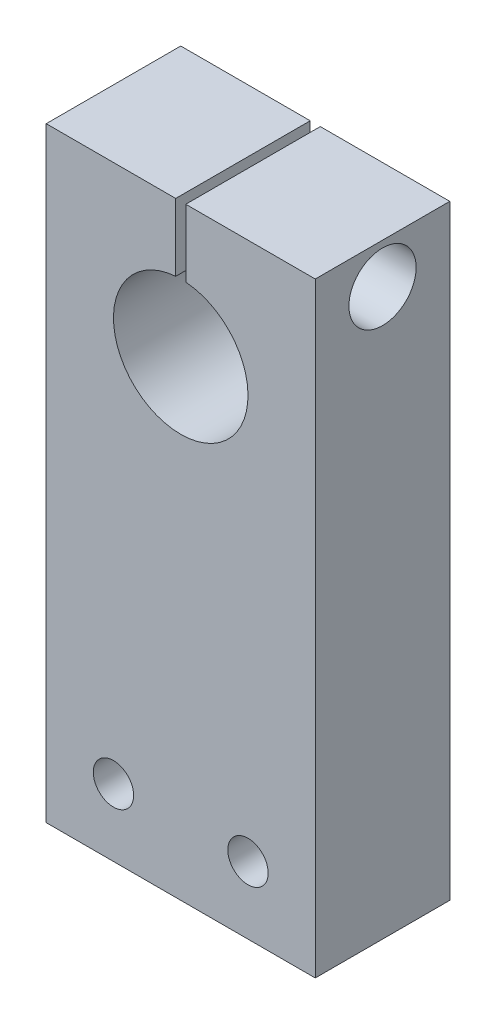
SolidWorks part; units mm, degrees
material "Aleación 1060"
ref_plane "Alzado" through (0, 0, 0) normal (0, 0, 1) x (1, 0, 0)
ref_plane "Planta" through (0, 0, 0) normal (0, 1, 0) x (1, 0, 0)
ref_plane "Vista lateral" through (0, 0, 0) normal (1, 0, 0) x (0, 0, -1)
sketch "Croquis1" plane through (0, 0, 0) normal (0, 0, 1) x (1, 0, 0)
  line L0 (-0.75, 34.9718) -> (-0.75, 45)
  line L1 (20, -45) -> (-20, -45) construction
  line L2 (20, -45) -> (20, 45) construction
  line L3 (20, 45) -> (-20, 45) construction
  line L4 (-20, -45) -> (-20, 45) construction
  line L5 (20, -45) -> (-20, 45) construction
  line L6 (20, 45) -> (-20, -45) construction
  line L7 (0.75, -6.3) -> (-0.75, -6.3) construction
  line L8 (0.75, -6.3) -> (0.75, 56.3) construction
  line L9 (0.75, 56.3) -> (-0.75, 56.3) construction
  line L10 (-0.75, -6.3) -> (-0.75, 56.3) construction
  line L11 (0.75, -6.3) -> (-0.75, 56.3) construction
  line L12 (0.75, 56.3) -> (-0.75, -6.3) construction
  line L13 (-0.75, 45) -> (-20, 45)
  line L14 (-20, 45) -> (-20, -45)
  line L15 (-20, -45) -> (20, -45)
  line L16 (20, -45) -> (20, 45)
  line L17 (20, 45) -> (0.75, 45)
  line L18 (0.75, 45) -> (0.75, 34.9718)
  line L19 (-20, -35) -> (20, -35) construction
  circle A0 centre (0, 25) radius 10 construction
  arc A1 (-0.75, 34.9718) -> (0.75, 34.9718) centre (0, 25) ccw
  circle A2 centre (-10, -35) radius 3
  circle A3 centre (10, -35) radius 3
  point P0 (0, 0)
  dimension "D3" = 25
  dimension "D6" = 20
  dimension "D7" = 20
  dimension "D1" = 90
  dimension "D2" = 40
  dimension "D4" = 62.6
  dimension "D5" = 1.5
  dimension "D8" = 10
extrude "Saliente-Extruir1" add sketch "Croquis1" along normal blind 20 contours A1 L0 L13 L14 L15 L16 L17 L18
sketch "Croquis2" plane through (20, 0, 0) normal (1, 0, 0) x (0, 0, -1)
  line L0 (-20, 45) -> (0, 45) construction
  circle A0 centre (-10, 39) radius 3
  dimension "D1" = 6
extrude "Cortar-Extruir1" cut sketch "Croquis2" against normal blind 30
sketch "Croquis3" plane through (20, 0, 0) normal (1, 0, 0) x (0, 0, -1)
  circle A0 centre (-10, 39) radius 5
extrude "Cortar-Extruir2" cut sketch "Croquis3" against normal blind 10
